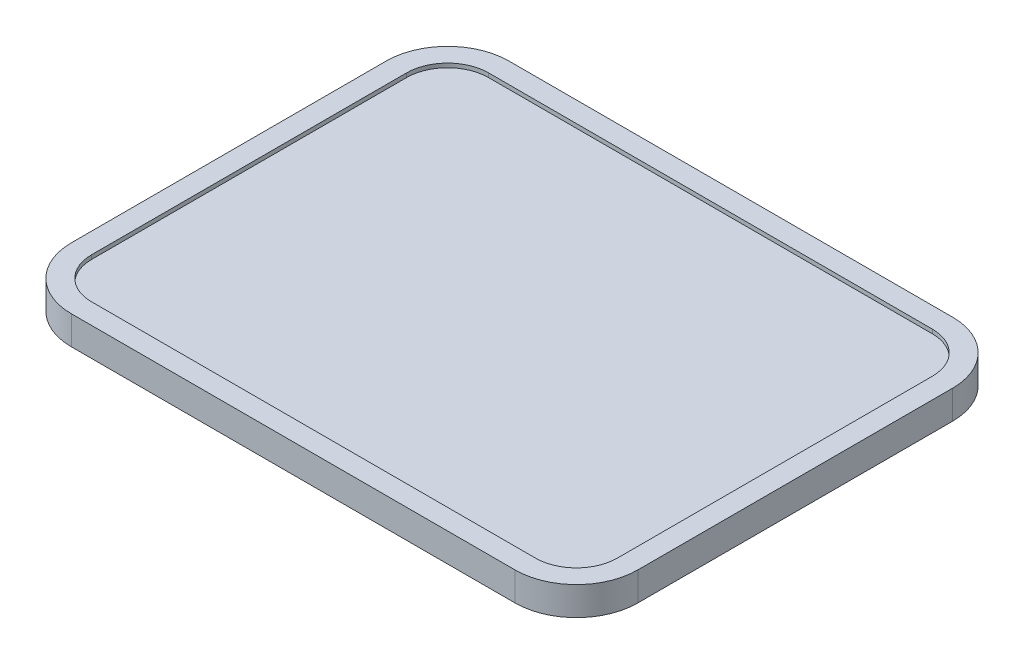
SolidWorks part; units mm, degrees
other "Markup1"
sketch "Sketch1" plane through (0, 0, 0) normal (0.5774, 0.5773, 0.5774) x (0.7071, 0, -0.7071)
sketch "Sketch2" plane through (0, 0, 0) normal (0.5774, 0.5773, 0.5774) x (0.7071, 0, -0.7071)
ref_plane "Front (z)" through (0, 0, 0) normal (0, 0, 1) x (1, 0, 0)
ref_plane "Top (y)" through (0, 0, 0) normal (0, 1, 0) x (1, 0, 0)
ref_plane "Right (x)" through (0, 0, 0) normal (1, 0, 0) x (0, 0, -1)
sketch "Sketch3" plane through (0, 0, 0) normal (0, 1, 0) x (1, 0, 0)
  line L1 (-138.5, -107) -> (138.5, -107)
  line L2 (-138.5, -107) -> (-138.5, 107)
  line L3 (-138.5, 107) -> (138.5, 107)
  line L4 (138.5, -107) -> (138.5, 107)
  line L5 (-138.5, -107) -> (138.5, 107) construction
  line L6 (-138.5, 107) -> (138.5, -107) construction
  point P0 (0, 0)
  dimension "D1" = 277
  dimension "D2" = 214
extrude "Boss-Extrude1" add sketch "Sketch3" along normal blind 14
fillet "Fillet1" radius 30 4 edges at (-138.5, 7, 107) (-138.5, 7, -107) (138.5, 7, -107) (138.5, 7, 107)
sketch "Sketch4" plane through (0, 14, 0) normal (0, 1, 0) x (1, 0, 0)
  line L8 (-128.5, 77) -> (-128.5, -77)
  line L9 (-108.5, -97) -> (108.5, -97)
  line L10 (128.5, -77) -> (128.5, 77)
  line L11 (108.5, 97) -> (-108.5, 97)
  line L12 (-128.5, 77) -> (-128.5, -77)
  line L13 (-108.5, -97) -> (108.5, -97)
  line L14 (128.5, -77) -> (128.5, 77)
  line L15 (108.5, 97) -> (-108.5, 97)
  arc A8 (-128.5, -77) -> (-108.5, -97) centre (-108.5, -77) ccw
  arc A9 (108.5, -97) -> (128.5, -77) centre (108.5, -77) ccw
  arc A10 (128.5, 77) -> (108.5, 97) centre (108.5, 77) ccw
  arc A11 (-108.5, 97) -> (-128.5, 77) centre (-108.5, 77) ccw
  arc A12 (-128.5, -77) -> (-108.5, -97) centre (-108.5, -77) ccw
  arc A13 (108.5, -97) -> (128.5, -77) centre (108.5, -77) ccw
  arc A14 (128.5, 77) -> (108.5, 97) centre (108.5, 77) ccw
  arc A15 (-108.5, 97) -> (-128.5, 77) centre (-108.5, 77) ccw
  dimension "D1" = 10
extrude "Cut-Extrude1" cut sketch "Sketch4" against normal blind 2
sketch "Sketch5" plane through (0, 0, 0) normal (0, -1, 0) x (1, 0, 0)
  line L2 (-104.5, 96) -> (104.5, 96)
  line L5 (-108.5, 107) -> (108.5, 107) construction
  line L6 (-138.5, 0) -> (138.5, 0) construction
  line L7 (-138.5, -77) -> (-138.5, 77) construction
  line L8 (138.5, 77) -> (138.5, -77) construction
  line L14 (-128.5, -77) -> (-128.5, 77)
  line L15 (128.5, 0) -> (128.5, -77)
  line L16 (-128.5, 77) -> (-104.5, 77)
  line L17 (-104.5, 77) -> (-104.5, 96)
  line L18 (0, -107) -> (0, 107) construction
  line L19 (104.5, 77) -> (104.5, 96)
  line L20 (128.5, 77) -> (104.5, 77)
  line L21 (128.5, 0) -> (128.5, 77)
  line L22 (128.5, -77) -> (104.5, -77)
  line L23 (104.5, -77) -> (104.5, -96)
  line L24 (-104.5, -77) -> (-104.5, -96)
  line L25 (-128.5, -77) -> (-104.5, -77)
  line L26 (-104.5, -96) -> (104.5, -96)
  point P19 (0, 0)
  dimension "D1" = 11
  dimension "D3" = 10
  dimension "D4" = 34
  dimension "D5" = 30
extrude "Cut-Extrude2" cut sketch "Sketch5" against normal blind 2
